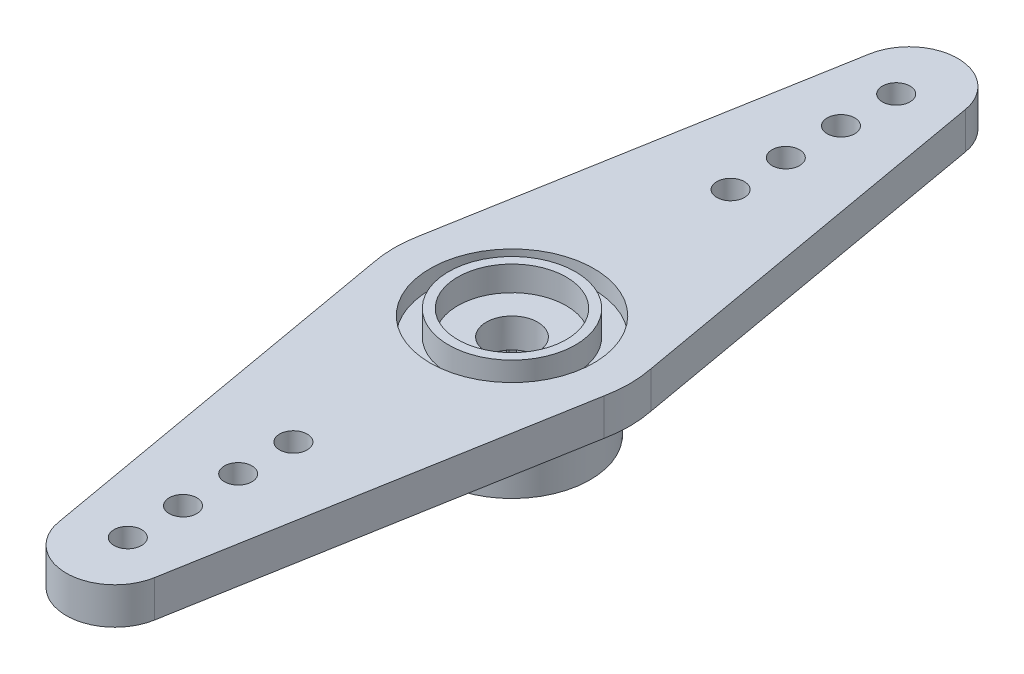
SolidWorks part; units mm, degrees
material "Polyethylene Cross-Linked"
ref_plane "Front Plane" through (0, 0, 0) normal (0, 0, 1) x (1, 0, 0)
ref_plane "Top Plane" through (0, 0, 0) normal (0, 1, 0) x (1, 0, 0)
ref_plane "Right Plane" through (0, 0, 0) normal (1, 0, 0) x (0, 0, -1)
sketch "Sketch1" plane through (0, 0, 0) normal (0, 1, 0) x (1, 0, 0)
  circle A0 centre (0, 0) radius 6.4
  dimension "D1" = 12.8
extrude "Boss-Extrude1" add sketch "Sketch1" along normal blind 5.6
sketch "Sketch2" plane through (0, 5.6, 0) normal (0, 1, 0) x (1, 0, 0)
  line L0 (0, 0) -> (0, 21.5829) construction
  line L1 (-2.6097, 22.0431) -> (-6.2717, 1.2749)
  line L2 (0, 25) -> (0, 21.5829) construction
  line L3 (2.6097, 22.0431) -> (6.2717, 1.2749)
  arc A0 (2.6097, 22.0431) -> (-2.6097, 22.0431) centre (0, 21.5829) ccw
  arc A4 (6.2717, 1.2749) -> (-6.2717, 1.2749) centre (0, 0) ccw
  circle A5 centre (0, 0) radius 6.4 construction
  point P1 (0, 19.2)
  point P5 (2.6097, 22.0431)
  point P12 (2.6097, 22.0431)
  dimension "D1" = 5.3
  dimension "D2" = 25
  dimension "D3" = 10
extrude "horn" add sketch "Sketch2" against normal blind 2
sketch "Sketch4" plane through (0, 5.6, 0) normal (0, -1, 0) x (-1, 0, 0)
  circle A0 centre (0, 0) radius 1.4
  dimension "D1" = 2.8
extrude "Cut-Extrude1" cut sketch "Sketch4" along normal through all
sketch "Sketch5" plane through (0, 0, 0) normal (0, -1, 0) x (-1, 0, 0)
  line L0 (0, 24.2329) -> (0, 20.8829) construction
  circle A0 centre (0, 20.8829) radius 0.75
  arc A1 (2.6097, 22.0431) -> (-2.6097, 22.0431) centre (0, 21.5829) ccw construction
  dimension "D1" = 1.5
  dimension "D2" = 3.35
extrude "Cut-Extrude2" cut sketch "Sketch5" against normal through all
sketch "Sketch6" plane through (0, 0, 0) normal (0, 1, 0) x (1, 0, 0)
  line L0 (0, 0) -> (0, 20.8829) construction
pattern_linear "LPattern1" count 4 spacing 3 along (0, 0, 1) of "Cut-Extrude2"
mirror "Mirror1" about plane through (0, 0, 0) normal (0, 0, 1) of "horn", "LPattern1", "Cut-Extrude2"
sketch "Sketch8" plane through (0, 0, 0) normal (0, -1, 0) x (-1, 0, 0)
  line L0 (0, -2.9) -> (0.2629, -2.5867)
  line L1 (0, -2.9) -> (-0.2629, -2.5867)
  line L2 (0, -2.6) -> (0, -2.9) construction
  line L3 (0, 0) -> (0, -2.6) construction
  arc A1 (-0.2629, -2.5867) -> (0.2629, -2.5867) centre (0, 0) ccw
  dimension "D1" = 0.3
  dimension "D2" = 5.2
  dimension "D3" = 80
extrude "Cut-Extrude4" cut sketch "Sketch8" against normal blind 3
pattern_circular "CirPattern2" count 26 over 360 about axis through (0, 0, 0) along (0, 1, 0) of "Cut-Extrude4"
sketch "Sketch9" plane through (0, 0, 0) normal (0, -1, 0) x (-1, 0, 0)
  circle A0 centre (0, 0) radius 2.6
  arc A1 (-0.2629, -2.5867) -> (0.2629, -2.5867) centre (0, 0) ccw construction
extrude "Cut-Extrude5" cut sketch "Sketch9" against normal blind 3
sketch "Sketch10" plane through (0, 0, 0) normal (0, -1, 0) x (-1, 0, 0)
  circle A0 centre (0, 0) radius 6.4
  circle A1 centre (0, 0) radius 4.25
  circle A2 centre (0, 0) radius 6.4 construction
  dimension "D1" = 8.5
extrude "Cut-Extrude6" cut sketch "Sketch10" against normal up to surface (3.6 mm away) up to face at (0, 3.6, 13.4877)
sketch "Sketch11" plane through (0, 0, 0) normal (0, 0, 1) x (1, 0, 0)
  line L2 (4.21, 1.69) -> (5.8127, 3.6)
  line L3 (6.2717, 3.6) -> (6.4, 3.6) construction
  line L4 (5.8127, 3.6) -> (4.21, 3.6)
  line L7 (4.21, 1.69) -> (4.16, 1.69)
  line L8 (4.16, 1.69) -> (4.16, 3.6)
  line L10 (4.21, 1.69) -> (4.21, 3.6) construction
  line L12 (4.16, 3.6) -> (4.21, 3.6)
  line L13 (0, 3.6) -> (4.16, 3.6) construction
  line L14 (-4.25, 3.6) -> (4.25, 3.6) construction
  dimension "D1" = 1.91
  dimension "D2" = 0.05
  dimension "D3" = 40
  dimension "D4" = 4.16
sketch "Sketch12" plane through (0, 5.6, 0) normal (0, 1, 0) x (1, 0, 0)
  circle A0 centre (0, 0) radius 4.45
  dimension "D1" = 8.9
extrude "Cut-Extrude7" cut sketch "Sketch12" against normal blind 1
sketch "Sketch13" plane through (0, 4.6, 0) normal (0, 1, 0) x (1, 0, 0)
  circle A0 centre (0, 0) radius 2.95
  circle A1 centre (0, 0) radius 3.45
  dimension "D1" = 0.5
  dimension "D2" = 6.9
extrude "Boss-Extrude6" add sketch "Sketch13" along normal up to surface (1 mm away)
sketch "Sketch14" plane through (0, 5.6, 0) normal (0, 1, 0) x (1, 0, 0)
  circle A0 centre (0, 0) radius 2.95
  circle A1 centre (0, 0) radius 2.95 construction
  circle A2 centre (0, 0) radius 3.45
  circle A3 centre (0, 0) radius 3.45 construction
extrude "Boss-Extrude7" add sketch "Sketch14" along normal blind 0.35
